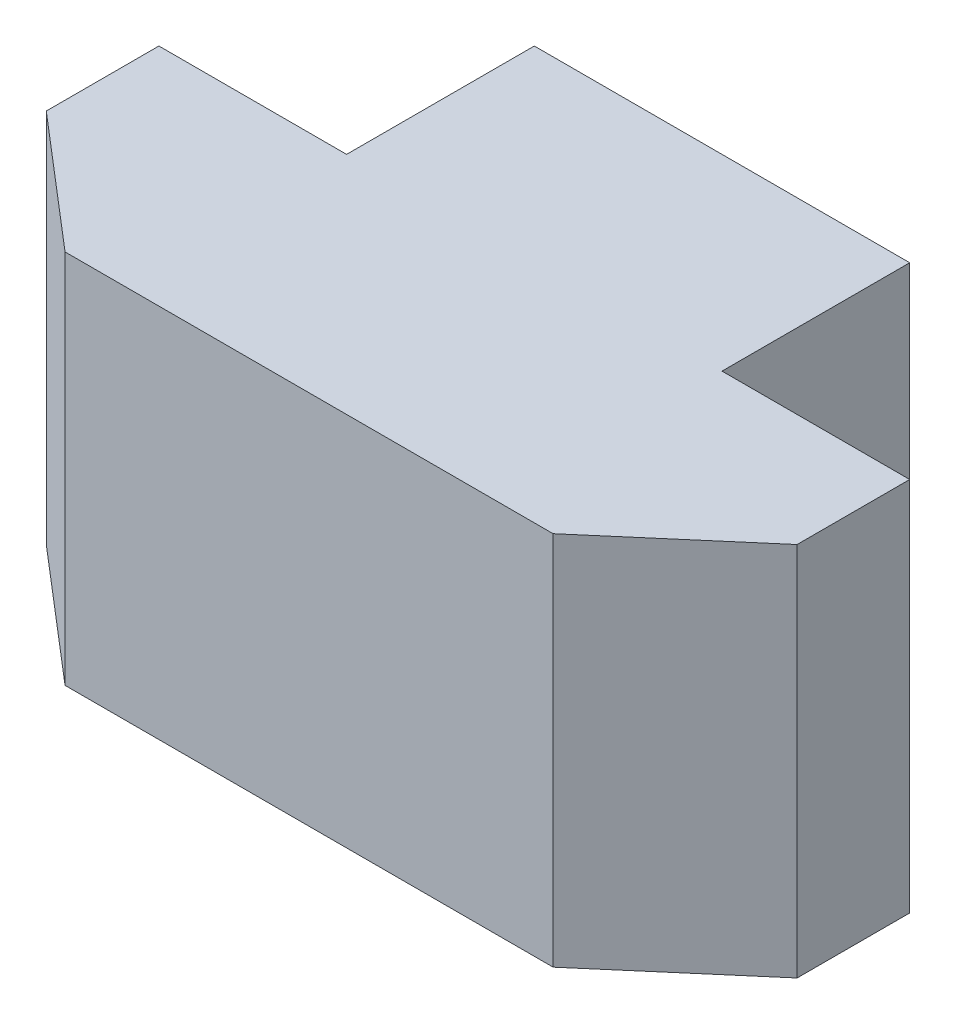
SolidWorks part; units mm, degrees
ref_plane "Front Plane" through (0, 0, 0) normal (0, 0, 1) x (1, 0, 0)
ref_plane "Top Plane" through (0, 0, 0) normal (0, 1, 0) x (1, 0, 0)
ref_plane "Right Plane" through (0, 0, 0) normal (1, 0, 0) x (0, 0, -1)
sketch "Sketch1" plane through (0, 0, 0) normal (0, 1, 0) x (1, 0, 0)
  line L0 (-7.6708, 1.2532) -> (2.3292, 1.2532)
  line L1 (2.3292, 1.2532) -> (2.3292, -3.7468)
  line L2 (-7.6708, 1.2532) -> (-7.6708, -3.7468)
  line L3 (-7.6708, -3.7468) -> (-12.6708, -3.7468)
  line L4 (2.3292, -3.7468) -> (7.3292, -3.7468)
  line L8 (-12.6708, -3.7468) -> (-12.6708, -6.7468)
  line L11 (-12.6708, -6.7468) -> (-9.1708, -9.7468)
  line L12 (-9.1708, -9.7468) -> (3.8292, -9.7468)
  line L13 (7.3292, -3.7468) -> (7.3292, -6.7468)
  line L14 (7.3292, -6.7468) -> (3.8292, -9.7468)
extrude "Boss-Extrude1" add sketch "Sketch1" along normal mid plane 10
